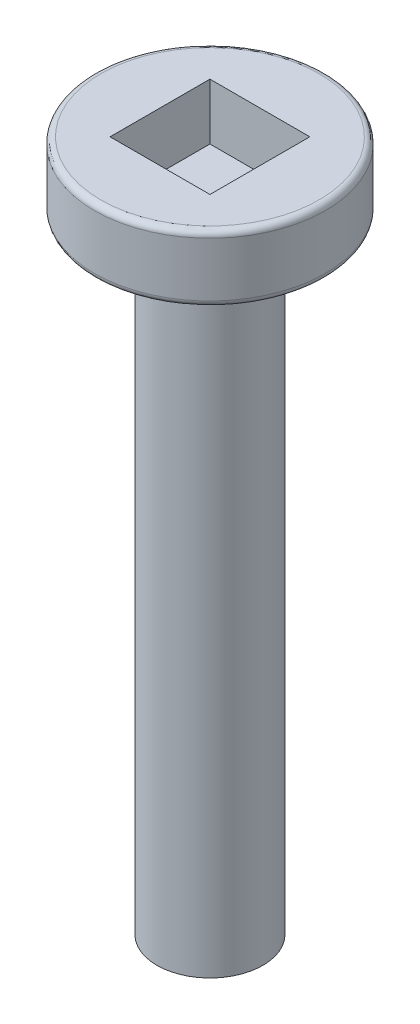
SolidWorks part; units mm, degrees
ref_plane "Front Plane" through (0, 0, 0) normal (0, 0, 1) x (1, 0, 0)
ref_plane "Top Plane" through (0, 0, 0) normal (0, 1, 0) x (1, 0, 0)
ref_plane "Right Plane" through (0, 0, 0) normal (1, 0, 0) x (0, 0, -1)
sketch "Sketch1" plane through (0, 0, 0) normal (0, 1, 0) x (1, 0, 0)
  circle A0 centre (0, 0) radius 4.699
  dimension "D1" = 9.398
extrude "Boss-Extrude1" add sketch "Sketch1" against normal blind 2.7178
sketch "Sketch2" plane through (0, 0, 0) normal (0, 1, 0) x (1, 0, 0)
  circle A0 centre (0, 0) radius 2.159
  dimension "D1" = 4.318
extrude "Boss-Extrude2" add sketch "Sketch2" against normal blind 28.1178
sketch "Sketch3" plane through (0, 0, 0) normal (0, 1, 0) x (1, 0, 0)
  line L1 (-2.032, 2.032) -> (2.032, 2.032)
  line L2 (-2.032, 2.032) -> (-2.032, -2.032)
  line L3 (-2.032, -2.032) -> (2.032, -2.032)
  line L4 (2.032, 2.032) -> (2.032, -2.032)
  dimension "D1" = 4.064
  dimension "D2" = 4.064
  dimension "D3" = 2.032
  dimension "D4" = 2.032
extrude "Cut-Extrude1" cut sketch "Sketch3" against normal blind 2.286
fillet "Fillet2" radius 0.254 2 edges at (0, -2.7178, 4.699) (0, 0, 4.699)
